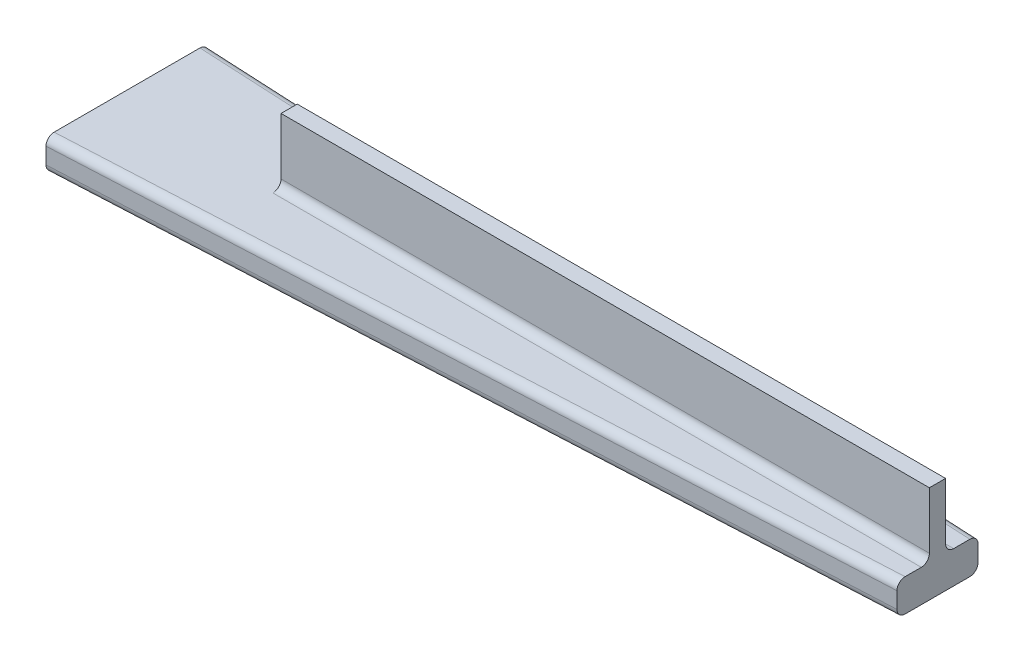
SolidWorks part; units mm, degrees
ref_plane "Front Plane" through (0, 0, 0) normal (0, 0, 1) x (1, 0, 0)
ref_plane "Top Plane" through (0, 0, 0) normal (0, 1, 0) x (1, 0, 0)
ref_plane "Right Plane" through (0, 0, 0) normal (1, 0, 0) x (0, 0, -1)
sketch "Sketch1" plane through (0, 0, 0) normal (0, 1, 0) x (1, 0, 0)
  line L4 (0, 0) -> (50, 0) construction
  line L5 (0, -5) -> (0, 5)
  line L6 (0, 5) -> (50, 2.5)
  line L7 (50, -2.5) -> (50, 2.5)
  line L8 (0, -5) -> (50, -2.5)
  point P6 (0, 0)
  point P11 (50, 0)
  dimension "D1" = 10
  dimension "D2" = 5
  dimension "D3" = 50
extrude "Boss-Extrude1" add sketch "Sketch1" along normal blind 2
sketch "Sketch2" plane through (0, 2, 0) normal (0, 1, 0) x (1, 0, 0)
  line L1 (50, -0.5) -> (50, 0.5)
  line L6 (50, -2.5) -> (50, 2.5) construction
  line L7 (50, 0.5) -> (10, 0.5)
  line L8 (10, 0.5) -> (10, -0.5)
  line L9 (10, -0.5) -> (50, -0.5)
  point P5 (50, 0)
  dimension "D1" = 1
  dimension "D2" = 40
  dimension "D3" = 2.5
extrude "Boss-Extrude2" add sketch "Sketch2" along normal blind 4
fillet "Fillet1" radius 0.5 6 edges at (25, 0, -3.75) (25, 2, -3.75) (25, 0, 3.75) (25, 2, 3.75) (30, 2, -0.5) (30, 2, 0.5)
